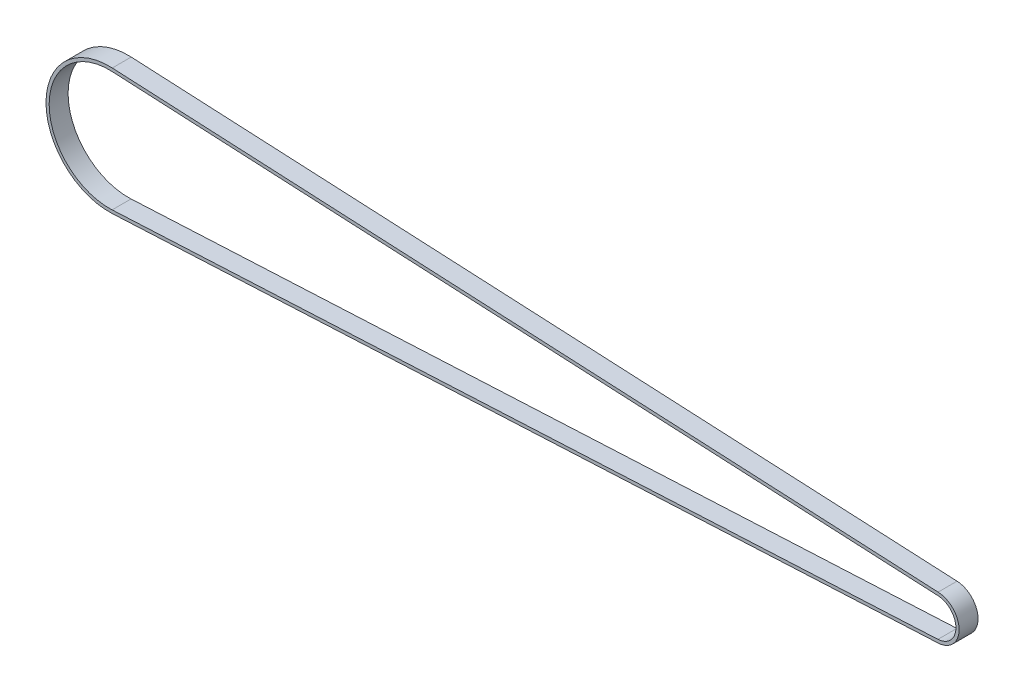
SolidWorks part; units mm, degrees
ref_plane "Front Plane" through (0, 0, 0) normal (0, 0, 1) x (1, 0, 0)
ref_plane "Top Plane" through (0, 0, 0) normal (0, 1, 0) x (1, 0, 0)
ref_plane "Right Plane" through (0, 0, 0) normal (1, 0, 0) x (0, 0, -1)
sketch "Sketch1" plane through (0, 0, 0) normal (0, 0, 1) x (1, 0, 0)
  line L0 (-65.8277, 19.9754) -> (195.7942, 6.9914)
  line L1 (-65.8277, -19.9754) -> (195.7942, -6.9914)
  line L2 (195.7446, 5.9926) -> (-65.8773, 18.9766)
  line L3 (-65.8773, -18.9766) -> (195.7446, -5.9926)
  arc A0 (-65.8277, 19.9754) -> (-65.8277, -19.9754) centre (-66.819, 0) ccw
  arc A1 (195.7942, 6.9914) -> (195.7942, -6.9914) centre (195.4472, 0) cw
  arc A2 (-65.8773, 18.9766) -> (-65.8773, -18.9766) centre (-66.819, 0) ccw
  arc A3 (195.7446, 5.9926) -> (195.7446, -5.9926) centre (195.4472, 0) cw
  point P11 (204.2232, 5.9928)
  point P12 (209.6896, 5.9928)
  point P13 (201.7937, 5.9928)
  point P14 (0, 0)
  dimension "D1" = 7
  dimension "D2" = 20
  dimension "D3" = 610
  dimension "D6" = 19
  dimension "D7" = 6
extrude "Boss-Extrude1" add sketch "Sketch1" along normal blind 6
